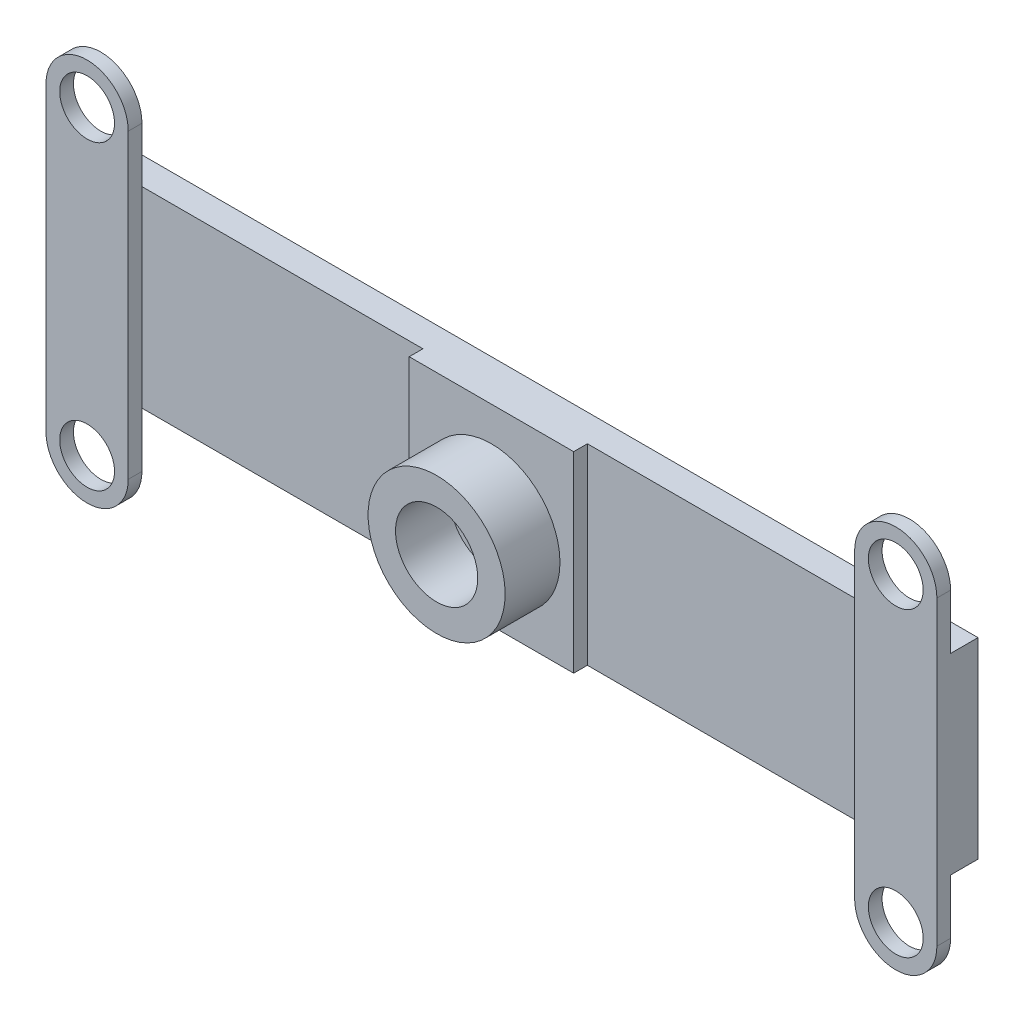
SolidWorks part; units mm, degrees
ref_plane "Plano frontal" through (0, 0, 0) normal (0, 0, 1) x (1, 0, 0)
ref_plane "Plano superior" through (0, 0, 0) normal (0, 1, 0) x (1, 0, 0)
ref_plane "Plano direito" through (0, 0, 0) normal (1, 0, 0) x (0, 0, -1)
sketch "Esboço1" plane through (0, 0, 0) normal (0, 0, 1) x (1, 0, 0)
  line L1 (-39.4355, 17.3215) -> (25.5645, 17.3215)
  line L2 (-39.4355, 17.3215) -> (-39.4355, 3.3215)
  line L3 (-39.4355, 3.3215) -> (25.5645, 3.3215)
  line L4 (25.5645, 17.3215) -> (25.5645, 3.3215)
  circle A0 centre (-6.9355, 10.3215) radius 2
  point P4 (0, 0)
  point P9 (0, 0)
  dimension "D4" = 4
  dimension "D3" = 32.5
  dimension "D5" = 7
  dimension "D1" = 14
  dimension "D2" = 65
extrude "Ressalto-extrusão1" add sketch "Esboço1" along normal blind 2
sketch "Esboço2" plane through (0, 0, 2) normal (0, 0, 1) x (1, 0, 0)
  line L6 (25.5645, 17.3215) -> (-39.4355, 17.3215) construction
  line L7 (-12.9355, 17.3215) -> (-0.9355, 17.3215)
  line L8 (-12.9355, 17.3215) -> (-12.9355, 3.3215)
  line L9 (-12.9355, 3.3215) -> (-0.9355, 3.3215)
  line L10 (-0.9355, 17.3215) -> (-0.9355, 3.3215)
  line L11 (-39.4355, 3.3215) -> (25.5645, 3.3215) construction
  line L12 (-39.4355, 17.3215) -> (-39.4355, 3.3215) construction
  line L13 (25.5645, 3.3215) -> (25.5645, 17.3215) construction
  line L14 (-33.4355, 21.3215) -> (-33.4355, -0.6785)
  line L16 (-39.4355, 21.3215) -> (-39.4355, -0.6785)
  line L30 (25.5645, 21.3215) -> (25.5645, -0.6785)
  line L32 (19.5645, 21.3215) -> (19.5645, -0.6785)
  circle A2 centre (-6.9355, 10.3215) radius 2
  arc A3 (-33.4355, 21.3215) -> (-39.4355, 21.3215) centre (-36.4355, 21.3215) ccw
  arc A4 (-39.4355, -0.6785) -> (-33.4355, -0.6785) centre (-36.4355, -0.6785) ccw
  arc A5 (19.5645, -0.6785) -> (25.5645, -0.6785) centre (22.5645, -0.6785) ccw
  arc A6 (25.5645, 21.3215) -> (19.5645, 21.3215) centre (22.5645, 21.3215) ccw
  circle A7 centre (-36.4355, 21.3215) radius 2
  circle A8 centre (-36.4355, -0.6785) radius 2
  circle A9 centre (22.5645, -0.6785) radius 2
  circle A10 centre (22.5645, 21.3215) radius 2
  dimension "D3" = 4
  dimension "D4" = 4
  dimension "D5" = 4
  dimension "D6" = 4
  dimension "D7" = 3
  dimension "D8" = 4
  dimension "D9" = 3
  dimension "D11" = 3
  dimension "D12" = 6
  dimension "D13" = 7
  dimension "D14" = 22
  dimension "D1" = 26.5
  dimension "D2" = 26.5
  dimension "D10" = 0
extrude "Ressalto-extrusão2" add sketch "Esboço2" along normal blind 1
sketch "Esboço3" plane through (0, 0, 3) normal (0, 0, 1) x (1, 0, 0)
  line L0 (-0.9355, 17.3215) -> (-12.9355, 17.3215) construction
  line L14 (-12.9355, 17.3215) -> (-12.9355, 3.3215) construction
  circle A0 centre (-6.9355, 9.8215) radius 5
  circle A2 centre (-6.9355, 9.8215) radius 3
  point P4 (-6.9355, 17.3215)
  dimension "D1" = 7.5
  dimension "D2" = 6
  dimension "D3" = 6
extrude "Ressalto-extrusão3" add sketch "Esboço3" along normal blind 4
